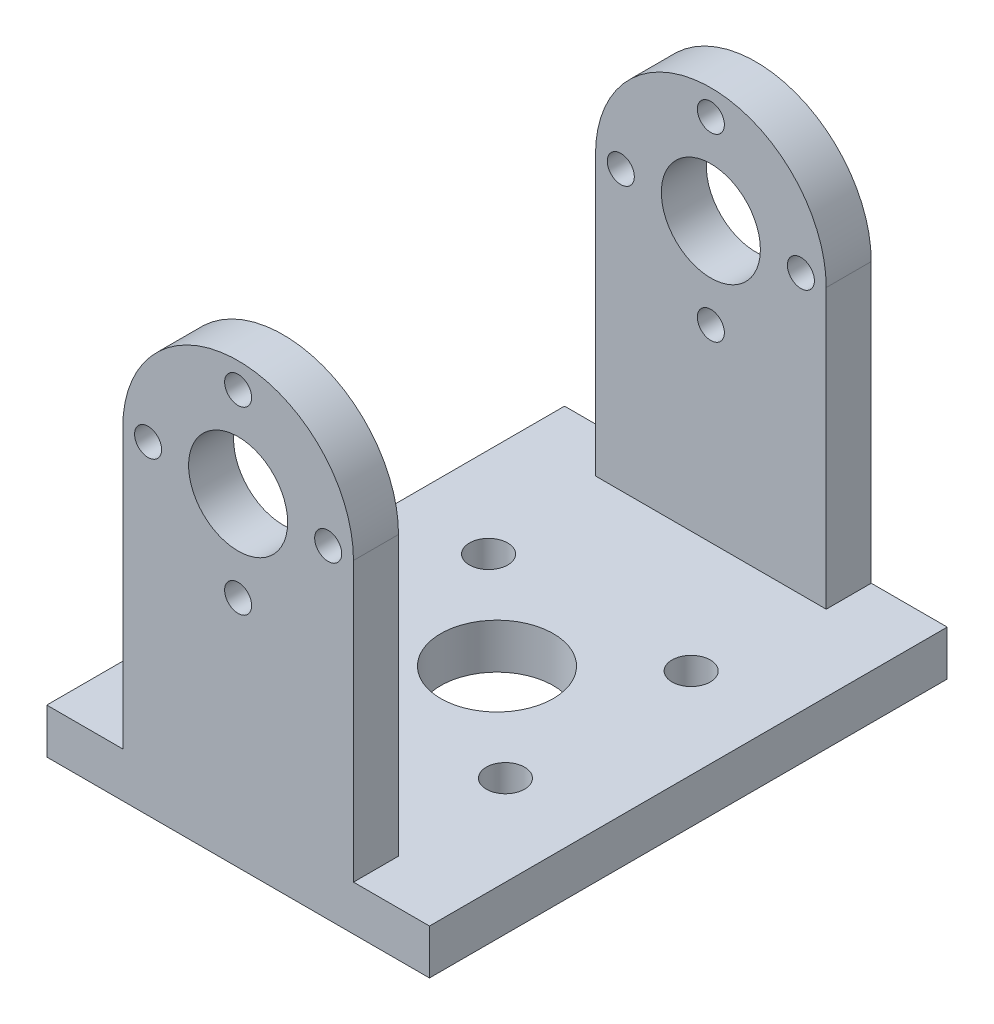
SolidWorks part; units mm, degrees
ref_plane "Front Plane" through (0, 0, 0) normal (0, 0, 1) x (1, 0, 0)
ref_plane "Top Plane" through (0, 0, 0) normal (0, 1, 0) x (1, 0, 0)
ref_plane "Right Plane" through (0, 0, 0) normal (1, 0, 0) x (0, 0, -1)
sketch "Sketch1" plane through (0, 0, 0) normal (0, 0, 1) x (1, 0, 0)
  line L0 (0, 0) -> (0, -68) construction
  line L1 (10.25, 0) -> (10.25, -68)
  line L2 (-10.25, 0) -> (-10.25, -68)
  line L3 (0, 0) -> (0, -68) construction
  line L4 (17, 0) -> (17, -68)
  line L5 (-17, 0) -> (-17, -68)
  line L7 (-10.25, -68) -> (10.25, -68)
  line L8 (-10.25, -68) -> (-10.25, -32.75)
  line L9 (-10.25, -32.75) -> (10.25, -32.75)
  line L10 (10.25, -68) -> (10.25, -32.75)
  line L11 (-17, -32.75) -> (17, -32.75)
  line L12 (-17, -32.75) -> (-17, -28.75)
  line L13 (-17, -28.75) -> (17, -28.75)
  line L14 (17, -32.75) -> (17, -28.75)
  line L15 (-10.25, -68) -> (10.25, -68)
  line L16 (-10.25, -68) -> (-10.25, -79.25)
  line L17 (-10.25, -79.25) -> (10.25, -79.25)
  line L18 (10.25, -68) -> (10.25, -79.25)
  arc A0 (10.25, 0) -> (-10.25, 0) centre (0, 0) ccw
  arc A1 (-10.25, -68) -> (10.25, -68) centre (0, -68) ccw
  arc A2 (17, 0) -> (-17, 0) centre (0, 0) ccw
  arc A3 (-17, -68) -> (17, -68) centre (0, -68) ccw
  circle A4 centre (0, 0) radius 8
  circle A5 centre (0, 8) radius 1.2
  circle A6 centre (8, 0) radius 1.2
  circle A7 centre (0, -8) radius 1.2
  circle A8 centre (-8, 0) radius 1.2
  circle A9 centre (0, -68) radius 10.25
  circle A10 centre (0, 0) radius 4.4
  point P3 (0, -34)
  point P10 (0, -34)
  point P28 (0, 0)
  dimension "D2" = 10.25
  dimension "D3" = 17
  dimension "D4" = 16
  dimension "D5" = 2.4
  dimension "D10" = 8.8
  dimension "D1" = 68
  dimension "D7" = 35.25
  dimension "D8" = 4
  dimension "D9" = 11.25
  dimension "D6" = 4
extrude "Boss-Extrude1" add sketch "Sketch1" along normal blind 4 contours A8 A4 A7 A6 A5 A10 | L1 A0 L2 L13 A8 A4 A5 A6 A7
sketch "Sketch3" plane through (0, -28.75, 0) normal (0, -1, 0) x (-1, 0, 0)
  line L21 (-10.25, -4) -> (-10.25, 0) construction
  line L22 (-17, 0) -> (17, 0)
  line L23 (-17, 0) -> (-17, -46)
  line L24 (-17, -46) -> (17, -46)
  line L25 (17, 0) -> (17, -46)
  line L28 (10.25, 0) -> (-10.25, 0) construction
  circle A0 centre (0, -23) radius 5
  circle A1 centre (-9, -14.75) radius 1.7
  circle A2 centre (9, -14.75) radius 1.7
  circle A3 centre (9, -31.25) radius 1.7
  circle A4 centre (-9, -31.25) radius 1.7
  dimension "D3" = 3.4
  dimension "D4" = 8.25
  dimension "D5" = 9
  dimension "D8" = 23
  dimension "D10" = 9
  dimension "D11" = 8.25
  dimension "D13" = 17
  dimension "D1" = 34
  dimension "D2" = 6.75
  dimension "D9" = 46
  dimension "D12" = 0
  dimension "D6" = 2
  dimension "D7" = 2
extrude "Boss-Extrude3" add sketch "Sketch3" against normal blind 4
ref_plane "Plane1" through (0, 0, 23) normal (0, 0, 1) x (1, 0, 0)
mirror "Mirror1" about plane through (0, 0, 23) normal (0, 0, 1) of "Boss-Extrude1"
